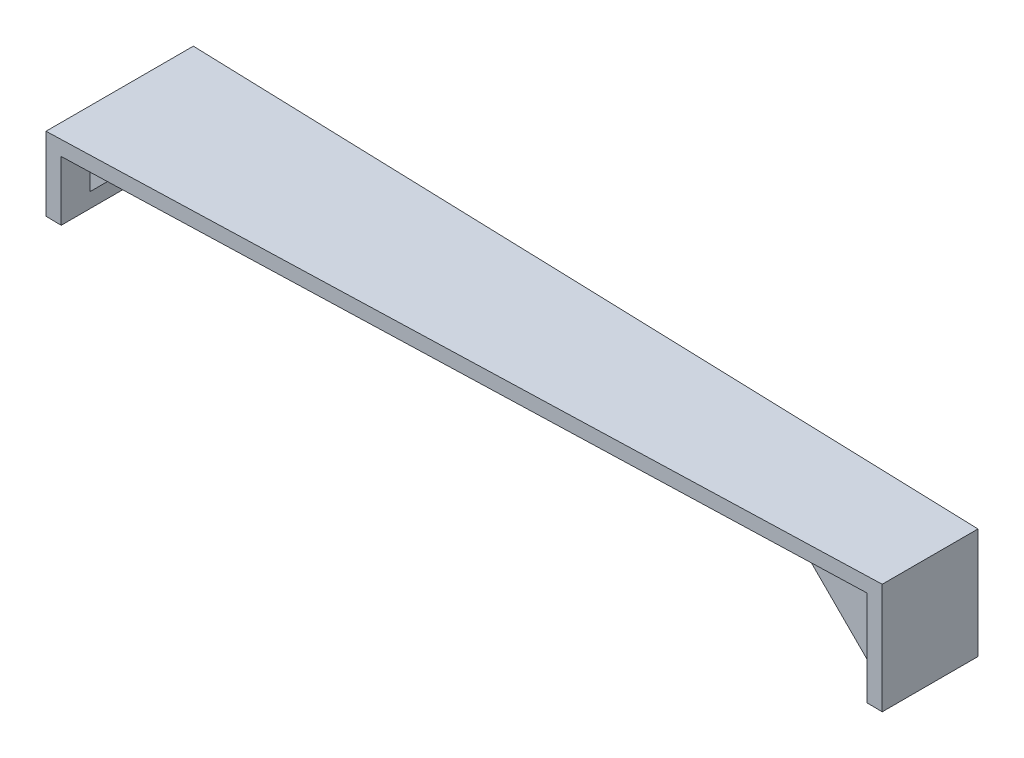
SolidWorks part; units mm, degrees
ref_plane "Front Plane" through (0, 0, 0) normal (0, 0, 1) x (1, 0, 0)
ref_plane "Top Plane" through (0, 0, 0) normal (0, 1, 0) x (1, 0, 0)
ref_plane "Right Plane" through (0, 0, 0) normal (1, 0, 0) x (0, 0, -1)
sketch "Sketch2" plane through (0, 0, 0) normal (0, 1, 0) x (1, 0, 0)
  line L0 (-55, 0) -> (55, 0) construction
  line L1 (55, -6.5) -> (-55, -10)
  line L2 (55, -6.5) -> (55, 6.5)
  line L3 (55, 6.5) -> (-55, 10)
  line L4 (-55, -10) -> (-55, 10)
  point P0 (0, 0)
  dimension "D1" = 20
  dimension "D2" = 13
  dimension "D3" = 110
extrude "Boss-Extrude1" add sketch "Sketch2" against normal blind 2
sketch "Sketch3" plane through (0, -2, 0) normal (0, -1, 0) x (1, 0, 0)
  line L0 (-53, 9.9364) -> (-53, -9.9364)
  line L1 (53, -6.5636) -> (53, 6.5636)
  line L2 (-53, 10) -> (-53, -10) construction
  line L3 (53, -6.5) -> (53, 6.5) construction
  line L12 (-55, 10) -> (-55, -10)
  line L13 (-55, -10) -> (55, -6.5)
  line L14 (55, -6.5) -> (55, 6.5)
  line L15 (55, 6.5) -> (-55, 10)
  line L16 (-55, 10) -> (-55, -10)
  line L17 (-55, -10) -> (-53, -9.9364)
  line L18 (55, -6.5) -> (55, 6.5)
  line L19 (55, 6.5) -> (53, 6.5636)
  line L20 (53, -6.5636) -> (55, -6.5)
  line L21 (-53, 9.9364) -> (-55, 10)
  dimension "D1" = 0
  dimension "D2" = 2
  dimension "D3" = 2
extrude "Boss-Extrude2" add sketch "Sketch3" along normal offset from surface (13 mm away) 15 up to face at (0, 0, 0)
sketch "Sketch5" plane through (0, 0, 0) normal (0, 0, 1) x (1, 0, 0)
  line L0 (-55, -10) -> (55, -15)
  line L1 (55, -15) -> (55, 0) construction
  line L3 (-55, 0) -> (55, 0) construction
  line L4 (-53, -2) -> (53, -2) construction
  line L5 (-55, -10) -> (-55, -25)
  line L6 (-55, -25) -> (55, -25)
  line L7 (55, -25) -> (55, -15)
  line L8 (-55, -15) -> (-55, 0) construction
  dimension "D1" = 13
  dimension "D2" = 10
  dimension "D3" = 10
extrude "Cut-Extrude1" cut sketch "Sketch5" against normal through all both and the other way through all
sketch "Sketch6" plane through (0, 0, 0) normal (0, 0, 1) x (1, 0, 0)
  line L0 (-53, -8.0909) -> (-46.9091, -2)
  line L1 (-53, -10.0909) -> (-53, -2) construction
  line L2 (-46.9091, -2) -> (-53, -2)
  line L3 (-53, -2) -> (-53, -8.0909)
  line L4 (53, -10.9091) -> (53, -2)
  line L5 (53, -14.9091) -> (53, -2) construction
  line L6 (53, -2) -> (44.0909, -2)
  line L7 (-53, -2) -> (53, -2) construction
  line L8 (44.0909, -2) -> (53, -10.9091)
  dimension "D1" = 45
  dimension "D2" = 45
  dimension "D3" = 2
  dimension "D4" = 4
extrude "Boss-Extrude3" add sketch "Sketch6" along normal blind 2 from offset 4
mirror "Mirror1" about plane through (0, 0, 0) normal (0, 0, 1) of "Boss-Extrude3"
